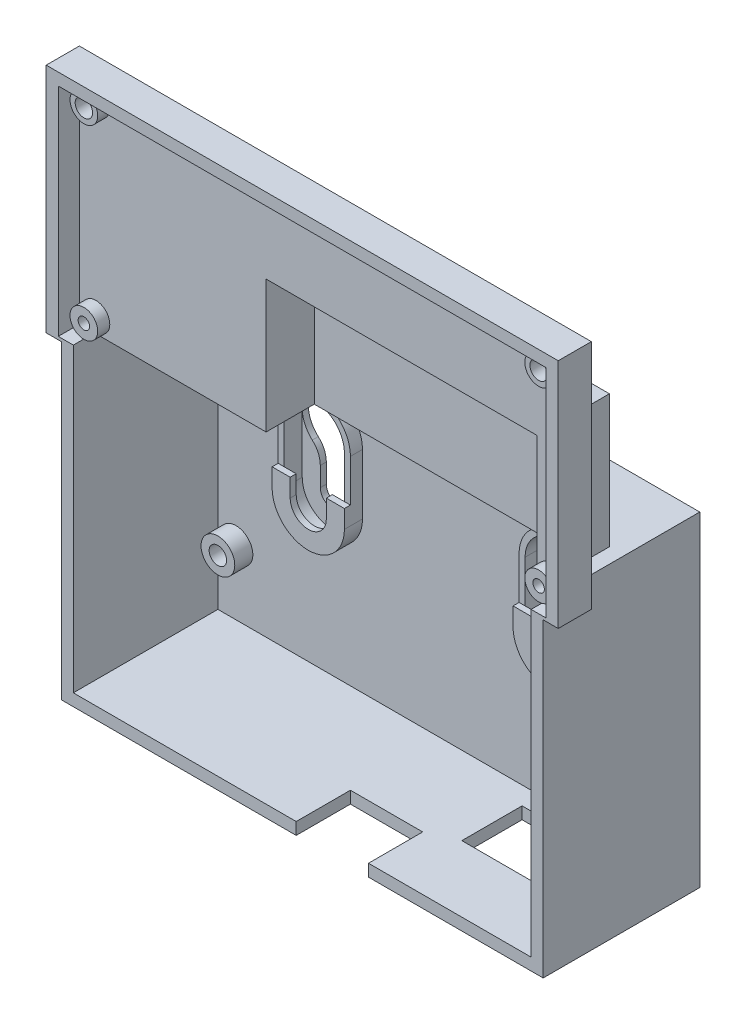
SolidWorks part; units mm, degrees
ref_plane "Спереди" through (0, 0, 0) normal (0, 0, 1) x (1, 0, 0)
ref_plane "Сверху" through (0, 0, 0) normal (0, 1, 0) x (1, 0, 0)
ref_plane "Справа" through (0, 0, 0) normal (1, 0, 0) x (0, 0, -1)
sketch "Эскиз1" plane through (0, 0, 0) normal (0, 0, 1) x (1, 0, 0)
  line L1 (-38, -25) -> (38, -25)
  line L2 (-38, -25) -> (-38, 25)
  line L3 (-38, 25) -> (38, 25)
  line L4 (38, -25) -> (38, 25)
  line L5 (-38, -25) -> (38, 25) construction
  line L6 (-38, 25) -> (38, -25) construction
  point P0 (0, 0)
extrude "Вытянуть-Тонкостенный1" add sketch "Эскиз1" along normal blind 24 thin
sketch "Эскиз2" plane through (0, 0, 0) normal (0, 0, -1) x (-1, 0, 0)
  line L1 (-40, -27) -> (40, -27)
  line L2 (-40, -27) -> (-40, 27)
  line L3 (-40, 27) -> (40, 27)
  line L4 (40, -27) -> (40, 27)
  line L5 (-40, -27) -> (40, 27) construction
  line L6 (-40, 27) -> (40, -27) construction
  point P4 (0, 0)
extrude "Бобышка-Вытянуть1" add sketch "Эскиз2" along normal blind 2
sketch "Эскиз3" plane through (0, 0, 0) normal (0, 0, 1) x (1, 0, 0)
  line L0 (35, 24.25) -> (37.5, 24.25) construction
  line L5 (-37.5, -24.25) -> (-35, -24.25) construction
  line L6 (-37.5, 24.25) -> (-37.5, -24.25) construction
  line L7 (35, 24.25) -> (35, 19.75) construction
  line L8 (-35, -24.25) -> (-35, -14.25) construction
  line L9 (-35, 19.75) -> (-35, 24.25) construction
  line L10 (-37.5, 24.25) -> (-35, 24.25) construction
  line L13 (37.5, -24.25) -> (37.5, -14.25) construction
  line L14 (-37.5, 24.25) -> (37.5, 24.25) construction
  line L16 (-37.5, -24.25) -> (37.5, -24.25) construction
  line L17 (37.5, 24.25) -> (37.5, -24.25) construction
  line L18 (-37.5, 24.25) -> (37.5, -24.25) construction
  line L19 (-37.5, -24.25) -> (37.5, 24.25) construction
  line L20 (37.5, -14.25) -> (35, -14.25) construction
  circle A0 centre (35, 19.75) radius 1.45
  circle A1 centre (35, -14.25) radius 1.45
  circle A2 centre (-35, 19.75) radius 1.45
  circle A3 centre (-35, -14.25) radius 1.45
  circle A4 centre (35, 19.75) radius 2.8
  circle A5 centre (35, -14.25) radius 2.8
  circle A6 centre (-35, -14.25) radius 2.8
  circle A7 centre (-35, 19.75) radius 2.8
  point P0 (0, 0)
  point P1 (0, 0)
extrude "Бобышка-Вытянуть4" add sketch "Эскиз3" along normal blind 3
sketch "Эскиз4" plane through (0, -27, 0) normal (0, -1, 0) x (1, 0, 0)
  line L0 (0, -2) -> (0, 3) construction
  line L1 (40, -2) -> (-40, -2) construction
  line L2 (-37.5, 3) -> (37.5, 3) construction
  line L3 (37.5, 3) -> (37.5, 13) construction
  line L4 (37.5, 13) -> (31.5, 13) construction
  line L5 (31.5, 13) -> (31.5, 3)
  line L6 (31.5, 3) -> (15.5, 3)
  line L7 (15.5, 3) -> (15.5, 13)
  line L8 (15.5, 13) -> (31.5, 13)
  line L9 (37.5, 3) -> (37.5, 17) construction
  line L10 (37.5, 17) -> (8.5, 17) construction
  line L11 (-37.5, 17) -> (-37.5, 3) construction
  line L12 (-37.5, 17) -> (1.5, 17) construction
  line L13 (-37.5, 3) -> (-37.5, 22) construction
  line L14 (-37.5, 22) -> (37.5, 22) construction
  line L15 (37.5, 22) -> (37.5, 3) construction
  line L16 (8.5, 17) -> (8.5, 22) construction
  line L17 (1.5, 17) -> (1.5, 22) construction
  line L18 (1.5, 22) -> (8.5, 22) construction
  line L19 (1.5, 17) -> (8.5, 17) construction
  line L20 (1.5, 22) -> (8.5, 17) construction
  line L21 (1.5, 17) -> (8.5, 22) construction
  line L23 (11, 15) -> (-1, 15)
  line L24 (11, 15) -> (11, 24)
  line L25 (11, 24) -> (-1, 24)
  line L26 (-1, 15) -> (-1, 24)
  line L27 (11, 15) -> (-1, 24) construction
  line L28 (11, 24) -> (-1, 15) construction
  point P10 (0, 3)
  point P19 (5, 19.5)
extrude "Вырез-Вытянуть1" cut sketch "Эскиз4" against normal blind 2
sketch "Эскиз6" plane through (0, 27, 0) normal (0, 1, 0) x (1, 0, 0)
  line L0 (0, 2) -> (0, -3) construction
  line L1 (-40, 2) -> (40, 2) construction
  line L2 (37.5, -3) -> (-37.5, -3) construction
  line L3 (-37.5, -3) -> (-37.5, -4) construction
  line L4 (-37.5, -4) -> (-31.5, -4) construction
  line L5 (-31.5, -4) -> (-31.5, -16.5)
  line L6 (-31.5, -16.5) -> (-21.5, -16.5)
  line L7 (-21.5, -16.5) -> (-21.5, -4)
  line L8 (-21.5, -4) -> (-31.5, -4)
  point P8 (0, -3)
extrude "Вырез-Вытянуть2" cut sketch "Эскиз6" against normal blind 2
sketch "Эскиз7" plane through (0, 0, 0) normal (0, 0, 1) x (1, 0, 0)
  circle A0 centre (-35, 19.75) radius 1.45
  circle A1 centre (-35, -14.25) radius 1.45
  circle A2 centre (35, 19.75) radius 1.45
  circle A3 centre (35, -14.25) radius 1.45
extrude "Вырез-Вытянуть3" cut sketch "Эскиз7" against normal blind 2
sketch "Эскиз8" plane through (0, 27, 0) normal (0, 1, 0) x (1, 0, 0)
  line L0 (-26.5, -16.5) -> (-26.5, -18.5) construction
  line L1 (-31.5, -16.5) -> (-21.5, -16.5) construction
  line L2 (-40, 2) -> (40, 2) construction
  line L3 (-40.5, -18.5) -> (40.5, -18.5)
  line L4 (-40.5, -18.5) -> (-40.5, -24)
  line L5 (-40.5, -24) -> (40.5, -24)
  line L6 (40.5, -24) -> (40.5, -18.5)
  point P8 (0, -18.5)
  point P10 (0, 2)
  point P14 (0, -18.5)
extrude "Вырез-Вытянуть4" cut sketch "Эскиз8" against normal blind 2
sketch "Эскиз9" plane through (0, 0, 18.5) normal (0, 0, 1) x (1, 0, 0)
  line L0 (38, 25) -> (-38, 25) construction
  line L2 (42.5, 25) -> (42.5, 63)
  line L3 (42.5, 63) -> (-42.5, 63)
  line L4 (-42.5, 25) -> (-42.5, 63)
  line L5 (42.5, 25) -> (-42.5, 63) construction
  line L6 (42.5, 63) -> (-42.5, 25) construction
  line L7 (-42.5, 25) -> (-42.5, 24.5)
  line L8 (-42.5, 24.5) -> (-40, 24.5)
  line L9 (-40, 24.5) -> (-40, 25)
  line L10 (-40, 25) -> (40, 25)
  line L11 (40, 25) -> (40, 24.5)
  line L12 (40, 24.5) -> (42.5, 24.5)
  line L13 (42.5, 24.5) -> (42.5, 25)
  point P4 (0, 44)
  point P7 (0, 25)
  point P8 (0, 25)
extrude "Бобышка-Вытянуть5" add sketch "Эскиз9" along normal blind 2
sketch "Эскиз10" plane through (0, 0, 20.5) normal (0, 0, 1) x (1, 0, 0)
  line L2 (40.5, 25) -> (40.5, 61)
  line L3 (40.5, 61) -> (-40.5, 61)
  line L4 (-40.5, 61) -> (-40.5, 25)
  line L7 (-42.5, 25) -> (-42.5, 63)
  line L8 (-42.5, 63) -> (42.5, 63)
  line L9 (42.5, 63) -> (42.5, 25)
  line L10 (-40.5, 25) -> (-40, 25)
  line L11 (-42.5, 25) -> (-42.5, 24.5)
  line L12 (-42.5, 24.5) -> (-40, 24.5)
  line L13 (-40, 24.5) -> (-40, 25)
  line L14 (40.5, 25) -> (40, 25)
  line L15 (40, 25) -> (40, 24.5)
  line L16 (40, 24.5) -> (42.5, 24.5)
  line L17 (42.5, 24.5) -> (42.5, 25)
extrude "Бобышка-Вытянуть6" add sketch "Эскиз10" along normal blind 3.5
sketch "Эскиз11" plane through (0, 0, 20.5) normal (0, 0, 1) x (1, 0, 0)
  line L0 (40.5, 25) -> (35.5, 25) construction
  line L1 (35.5, 25) -> (35.5, 47)
  line L2 (35.5, 47) -> (-9.5, 47)
  line L3 (-9.5, 47) -> (-9.5, 25)
  line L4 (-38, 25) -> (38, 25) construction
  line L5 (-9.5, 25) -> (35.5, 25)
extrude "Вырез-Вытянуть5" cut sketch "Эскиз11" against normal blind 8
sketch "Эскиз12" plane through (0, 0, 18.5) normal (0, 0, -1) x (-1, 0, 0)
  line L0 (9.5, 27) -> (15.5, 27)
  line L1 (9.5, 27) -> (40, 27) construction
  line L2 (15.5, 27) -> (15.5, 49)
  line L3 (9.5, 47) -> (9.5, 49) construction
  line L4 (15.5, 49) -> (-37.5, 49)
  line L5 (-37.5, 49) -> (-37.5, 27)
  line L6 (-40, 27) -> (-35.5, 27) construction
  line L7 (-37.5, 27) -> (-35.5, 27)
  line L8 (-35.5, 27) -> (-35.5, 47)
  line L9 (-35.5, 47) -> (9.5, 47)
  line L10 (9.5, 47) -> (9.5, 27)
extrude "Бобышка-Вытянуть7" add sketch "Эскиз12" along normal blind 6
sketch "Эскиз13" plane through (0, 0, 12.5) normal (0, 0, -1) x (-1, 0, 0)
  line L1 (15.5, 49) -> (-37.5, 49)
  line L2 (15.5, 49) -> (15.5, 27)
  line L3 (15.5, 27) -> (-37.5, 27)
  line L4 (-37.5, 49) -> (-37.5, 27)
  line L5 (15.5, 49) -> (-37.5, 27) construction
  line L6 (15.5, 27) -> (-37.5, 49) construction
  point P4 (-11, 38)
extrude "Бобышка-Вытянуть8" add sketch "Эскиз13" along normal blind 2
sketch "Эскиз14" plane through (0, 0, 20.5) normal (0, 0, 1) x (1, 0, 0)
  line L0 (40.5, 61) -> (-40.5, 25) construction
  line L1 (-40.5, 61) -> (40.5, 25) construction
  line L5 (-37.75, 58.5) -> (37.75, 58.5) construction
  line L6 (-37.75, 58.5) -> (-37.75, 27.5) construction
  line L7 (-37.75, 27.5) -> (37.75, 27.5) construction
  line L8 (37.75, 58.5) -> (37.75, 27.5) construction
  line L9 (-37.75, 58.5) -> (37.75, 27.5) construction
  line L10 (-37.75, 27.5) -> (37.75, 58.5) construction
  circle A0 centre (37.75, 58.5) radius 1.45
  circle A1 centre (37.75, 27.5) radius 0.95
  circle A2 centre (-37.75, 58.5) radius 1.45
  circle A3 centre (-37.75, 27.5) radius 0.95
  circle A4 centre (37.75, 58.5) radius 2.3
  circle A5 centre (37.75, 27.5) radius 2.3
  circle A6 centre (-37.75, 58.5) radius 2.3
  circle A7 centre (-37.75, 27.5) radius 2.3
  point P6 (0, 43)
extrude "Бобышка-Вытянуть9" add sketch "Эскиз14" along normal blind 2
sketch "Эскиз15" plane through (0, 0, 20.5) normal (0, 0, 1) x (1, 0, 0)
  circle A1 centre (-37.75, 58.5) radius 1.45
  circle A2 centre (37.75, 58.5) radius 1.45
extrude "Вырез-Вытянуть6" cut sketch "Эскиз15" against normal blind 2
sketch "Эскиз16" plane through (0, 0, 0) normal (0, 0, 1) x (1, 0, 0)
  line L0 (14, 10) -> (26, 10) construction
  line L3 (-20, 0) -> (20, 0) construction
  line L6 (-26, 10) -> (-14, 10) construction
  line L9 (-20, 8.9238) -> (-20, 10) construction
  line L10 (-25, 10) -> (-25, 0)
  line L11 (-15, 0) -> (-15, 10)
  line L12 (-14, 10) -> (-14, 0)
  line L13 (-26, 0) -> (-26, 10)
  line L14 (20, 10.5885) -> (20, 10) construction
  line L15 (15, 10) -> (15, 0)
  line L16 (25, 0) -> (25, 10)
  line L17 (26, 10) -> (26, 0)
  line L18 (14, 0) -> (14, 10)
  arc A2 (-15, 0) -> (-25, 0) centre (-20, 0) cw
  arc A4 (-15, 10) -> (-25, 10) centre (-20, 10) ccw
  arc A5 (-26, 10) -> (-14, 10) centre (-20, 10) cw
  arc A6 (-14, 0) -> (-26, 0) centre (-20, 0) cw
  arc A7 (25, 0) -> (15, 0) centre (20, 0) cw
  arc A8 (25, 10) -> (15, 10) centre (20, 10) ccw
  arc A9 (14, 10) -> (26, 10) centre (20, 10) cw
  arc A10 (26, 0) -> (14, 0) centre (20, 0) cw
  point P11 (0, 0)
  point P21 (-20, 10)
  point P24 (-20, 8.9238)
  point P30 (20, 10)
  point P33 (16.9274, 10.5885)
extrude "Бобышка-Вытянуть10" add sketch "Эскиз16" along normal blind 2
sketch "Эскиз17" plane through (0, 0, 0) normal (0, 0, 1) x (1, 0, 0)
  line L0 (-18, 2) -> (-18, 3.196)
  line L1 (-20, 0) -> (-18, 0) construction
  line L2 (-20, 0) -> (-22, 0) construction
  line L4 (-20, 9.9042) -> (-20, 0) construction
  line L6 (-18, 0) -> (-18, 2)
  line L7 (-22, 0) -> (-22, 2)
  line L10 (20, 0) -> (18, 0) construction
  line L11 (20, 0) -> (22, 0) construction
  line L12 (18, 0) -> (18, 2)
  line L13 (22, 2) -> (22, 0)
  line L22 (20, 10) -> (20, 5) construction
  line L23 (22, 2) -> (22, 10) construction
  line L24 (18, 2) -> (18, 10) construction
  line L25 (22, 3.2918) -> (22, 2)
  line L26 (18, 2) -> (18, 3.2918)
  line L27 (-22, 2) -> (-22, 3.196)
  arc A1 (-18, 0) -> (-22, 0) centre (-20, 0) cw
  arc A5 (25, 10) -> (15, 10) centre (20, 10) ccw construction
  arc A6 (22, 0) -> (18, 0) centre (20, 0) cw
  arc A9 (23.3333, 6.2732) -> (16.6667, 6.2732) centre (20, 10) ccw
  arc A10 (-16.6667, 6.1774) -> (-23.3333, 6.1774) centre (-20, 9.9042) ccw
  arc A11 (16.6667, 6.2732) -> (18, 3.2918) centre (14, 3.2918) cw
  arc A12 (22, 3.2918) -> (23.3333, 6.2732) centre (26, 3.2918) cw
  arc A13 (-23.3333, 6.1774) -> (-22, 3.196) centre (-26, 3.196) cw
  arc A14 (-18, 3.196) -> (-16.6667, 6.1774) centre (-14, 3.196) cw
  point P10 (-20, 0)
  point P12 (25, 10)
  point P14 (15, 10)
  point P30 (20, 5)
  point P32 (18, 5.4174)
  point P36 (22, 5.4174)
  point P42 (20, 0)
  point P43 (-20, 0)
  dimension "D1" = 4
extrude "Вырез-Вытянуть7" cut sketch "Эскиз17" against normal blind 2
sketch "Эскиз18" plane through (0, 0, 2) normal (0, 0, 1) x (1, 0, 0)
  line L16 (20, 0) -> (18, 0) construction
  line L17 (20, 0) -> (22, 0) construction
  line L18 (22, 0) -> (22, 3)
  line L21 (14, 0) -> (14, 3)
  line L22 (18, 0) -> (18, 3)
  line L23 (18, 3) -> (15, 3)
  line L24 (15, 10) -> (15, 0) construction
  line L25 (14, 10) -> (14, 0) construction
  line L26 (26, 0) -> (26, 3)
  line L27 (26, 0) -> (26, 10) construction
  line L29 (14, 3) -> (15, 3)
  line L30 (26, 3) -> (22, 3)
  line L31 (-14, 0) -> (-14, 3)
  line L32 (-14, 0) -> (-14, 10) construction
  line L33 (-14, 3) -> (-17, 3)
  line L34 (-17, 3) -> (-17, 0)
  line L35 (-17, 0) -> (-23, 0) construction
  line L36 (-23, 0) -> (-23, 3)
  line L37 (-23, 3) -> (-26, 3)
  line L38 (-26, 10) -> (-26, 0) construction
  line L39 (-26, 3) -> (-26, 0)
  arc A4 (14, 0) -> (26, 0) centre (20, 0) ccw
  arc A9 (18, 0) -> (22, 0) centre (20, 0) ccw
  arc A10 (-26, 0) -> (-14, 0) centre (-20, 0) ccw
  arc A11 (-23, 0) -> (-17, 0) centre (-20, 0) ccw
extrude "Бобышка-Вытянуть11" add sketch "Эскиз18" along normal blind 1
sketch "Эскиз19" plane through (0, 0, 0) normal (0, 0, 1) x (1, 0, 0)
  line L0 (-25, 0) -> (-25, 10)
  line L1 (-15, 10) -> (-15, 0)
  line L2 (25, 10) -> (25, 0)
  line L3 (15, 10) -> (15, 0)
  line L4 (15, 10) -> (15, 0) construction
  arc A0 (-25, 0) -> (-15, 0) centre (-20, 0) ccw
  arc A1 (-25, 10) -> (-15, 10) centre (-20, 10) cw
  arc A2 (25, 0) -> (15, 0) centre (20, 0) cw
  arc A3 (25, 10) -> (15, 10) centre (20, 10) ccw
extrude "Вырез-Вытянуть8" cut sketch "Эскиз19" against normal blind 1
sketch "Эскиз20" plane through (0, 0, -2) normal (0, 0, -1) x (-1, 0, 0)
  circle A0 centre (35, -14.25) radius 3
  circle A1 centre (35, 19.75) radius 3
  circle A2 centre (-35, -14.25) radius 3
  circle A3 centre (-35, 19.75) radius 3
extrude "Вырез-Вытянуть9" cut sketch "Эскиз20" against normal blind 1
sketch "Эскиз21" plane through (0, 0, 18.5) normal (0, 0, -1) x (-1, 0, 0)
  circle A0 centre (37.75, 58.5) radius 3
  circle A1 centre (-37.75, 58.5) radius 3
extrude "Вырез-Вытянуть10" cut sketch "Эскиз21" against normal blind 1
sketch "Эскиз27" plane through (0, 0, -2) normal (0, 0, -1) x (-1, 0, 0)
  line L0 (35, -14.25) -> (35, -27) construction
  line L1 (-40, -27) -> (40, -27) construction
  line L2 (35, -27) -> (40, -27) construction
